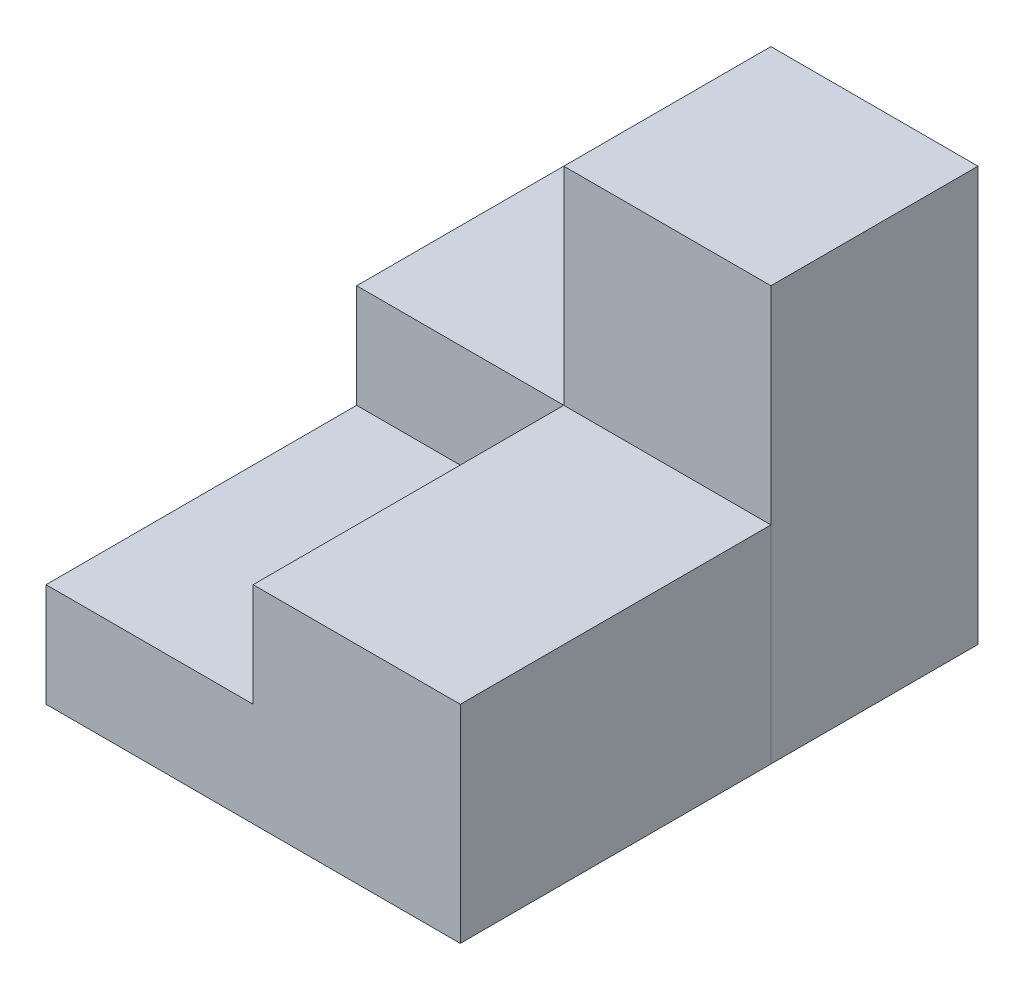
SolidWorks part; units mm, degrees
ref_plane "Front Plane" through (0, 0, 0) normal (0, 0, 1) x (1, 0, 0)
ref_plane "Top Plane" through (0, 0, 0) normal (0, 1, 0) x (1, 0, 0)
ref_plane "Right Plane" through (0, 0, 0) normal (1, 0, 0) x (0, 0, -1)
sketch "Sketch1" plane through (0, 0, 0) normal (0, 1, 0) x (1, 0, 0)
  line L7 (0, 0) -> (20, 0)
  line L8 (0, 0) -> (0, 20)
  line L9 (0, 20) -> (20, 20)
  line L10 (20, 0) -> (20, 20)
  dimension "D1" = 20
  dimension "D2" = 20
extrude "Boss-Extrude7" add sketch "Sketch1" along normal blind 40
sketch "Sketch5" plane through (0, 0, 0) normal (0, 1, 0) x (1, 0, 0)
  line L1 (0, 20) -> (-20, 20)
  line L2 (0, 20) -> (0, 0)
  line L3 (0, 0) -> (-20, 0)
  line L4 (-20, 20) -> (-20, 0)
  dimension "D1" = 20
  dimension "D2" = 20
extrude "Boss-Extrude8" add sketch "Sketch5" along normal blind 20
sketch "Sketch6" plane through (0, 0, 0) normal (0, 1, 0) x (1, 0, 0)
  line L1 (0, 0) -> (20.0038, 0)
  line L2 (0, 0) -> (0, -30)
  line L3 (0, -30) -> (20.0038, -30)
  line L4 (20.0038, 0) -> (20.0038, -30)
  dimension "D1" = 20.0038
  dimension "D2" = 30
extrude "Boss-Extrude9" add sketch "Sketch6" along normal blind 20
sketch "Sketch7" plane through (0, 0, 0) normal (0, 1, 0) x (1, 0, 0)
  line L1 (0, 0) -> (-20, 0)
  line L2 (0, 0) -> (0, -30)
  line L3 (0, -30) -> (-20, -30)
  line L4 (-20, 0) -> (-20, -30)
  dimension "D1" = 30
  dimension "D2" = 20
extrude "Boss-Extrude10" add sketch "Sketch7" along normal blind 10
